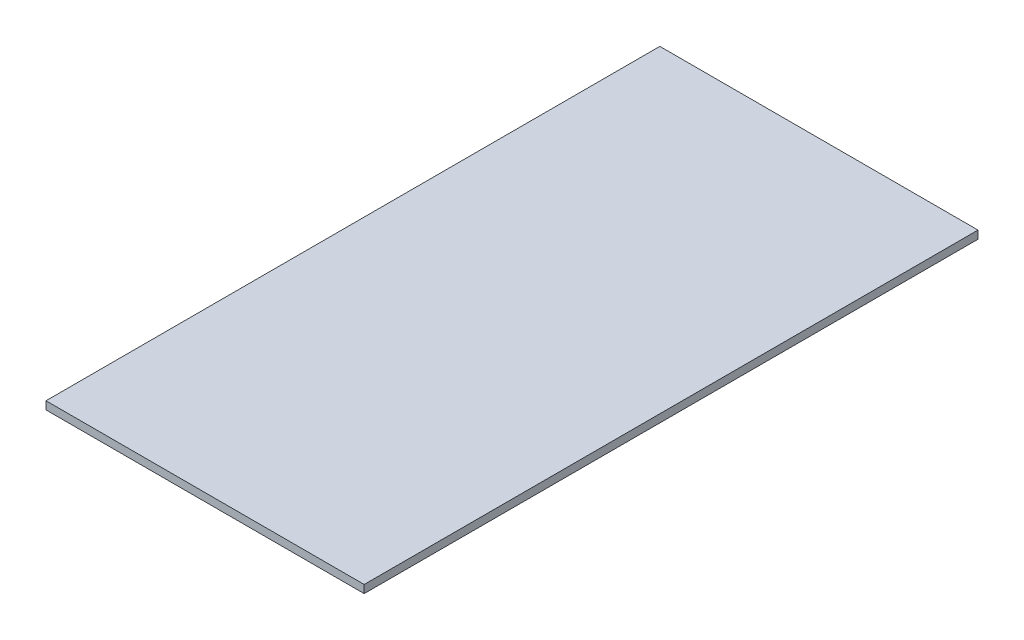
SolidWorks part; units mm, degrees
ref_plane "Front Plane" through (0, 0, 0) normal (0, 0, 1) x (1, 0, 0)
ref_plane "Top Plane" through (0, 0, 0) normal (0, 1, 0) x (1, 0, 0)
ref_plane "Right Plane" through (0, 0, 0) normal (1, 0, 0) x (0, 0, -1)
sketch "Sketch1" plane through (0, 0, 0) normal (0, 1, 0) x (1, 0, 0)
  line L1 (-60, -115.75) -> (60, -115.75)
  line L2 (-60, -115.75) -> (-60, 115.75)
  line L3 (-60, 115.75) -> (60, 115.75)
  line L4 (60, -115.75) -> (60, 115.75)
  line L5 (-60, -115.75) -> (60, 115.75) construction
  line L6 (-60, 115.75) -> (60, -115.75) construction
  point P0 (0, 0)
  dimension "D1" = 231.5
  dimension "D2" = 120
extrude "Boss-Extrude1" add sketch "Sketch1" along normal blind 3
